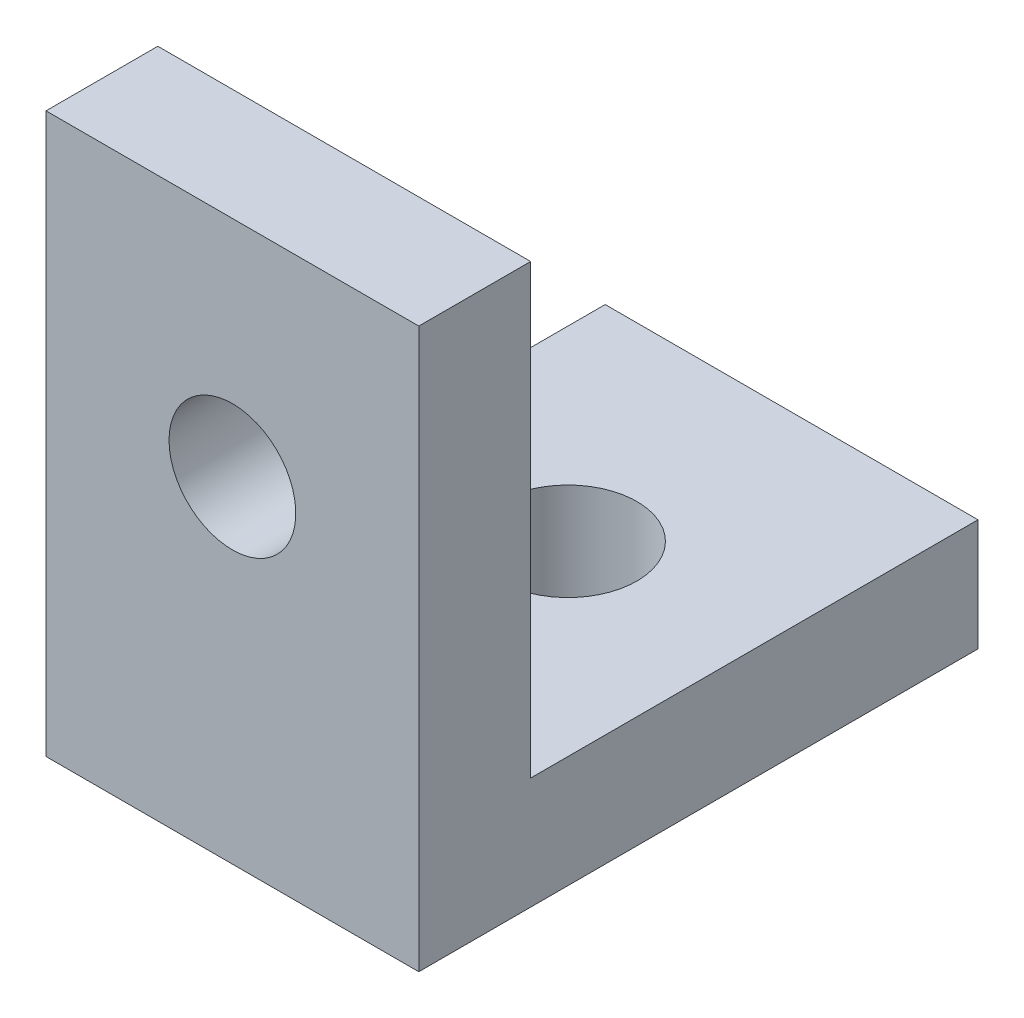
SolidWorks part; units mm, degrees
material "Onyx"
ref_plane "Front Plane" through (0, 0, 0) normal (0, 0, 1) x (1, 0, 0)
ref_plane "Top Plane" through (0, 0, 0) normal (0, 1, 0) x (1, 0, 0)
ref_plane "Right Plane" through (0, 0, 0) normal (1, 0, 0) x (0, 0, -1)
sketch "Sketch1" plane through (0, 0, 0) normal (1, 0, 0) x (0, 0, -1)
  line L0 (-3, 12) -> (0, 12)
  line L1 (0, 12) -> (0, 0)
  line L2 (0, 0) -> (12, 0)
  line L3 (12, 0) -> (12, -3)
  line L4 (12, -3) -> (-3, -3)
  line L5 (-3, -3) -> (-3, 12)
  dimension "D1" = 3
  dimension "D2" = 3
  dimension "D3" = 15
  dimension "D4" = 15
extrude "Boss-Extrude1" add sketch "Sketch1" along normal blind 10
sketch "Sketch2" plane through (0, 0, 0) normal (0, 1, 0) x (1, 0, 0)
  line L0 (0, 12) -> (10, 0) construction
  line L1 (10, 12) -> (0, 0) construction
  circle A0 centre (5, 6) radius 1.85
  dimension "D1" = 3.7
extrude "Cut-Extrude1" cut sketch "Sketch2" against normal through all
sketch "Sketch4" plane through (0, 0, 0) normal (0, 0, -1) x (-1, 0, 0)
  line L0 (-10, 12) -> (0, 0) construction
  line L1 (0, 12) -> (-10, 0) construction
  circle A0 centre (-5, 6) radius 1.7
  dimension "D1" = 3.4
extrude "Cut-Extrude2" cut sketch "Sketch4" against normal through all
